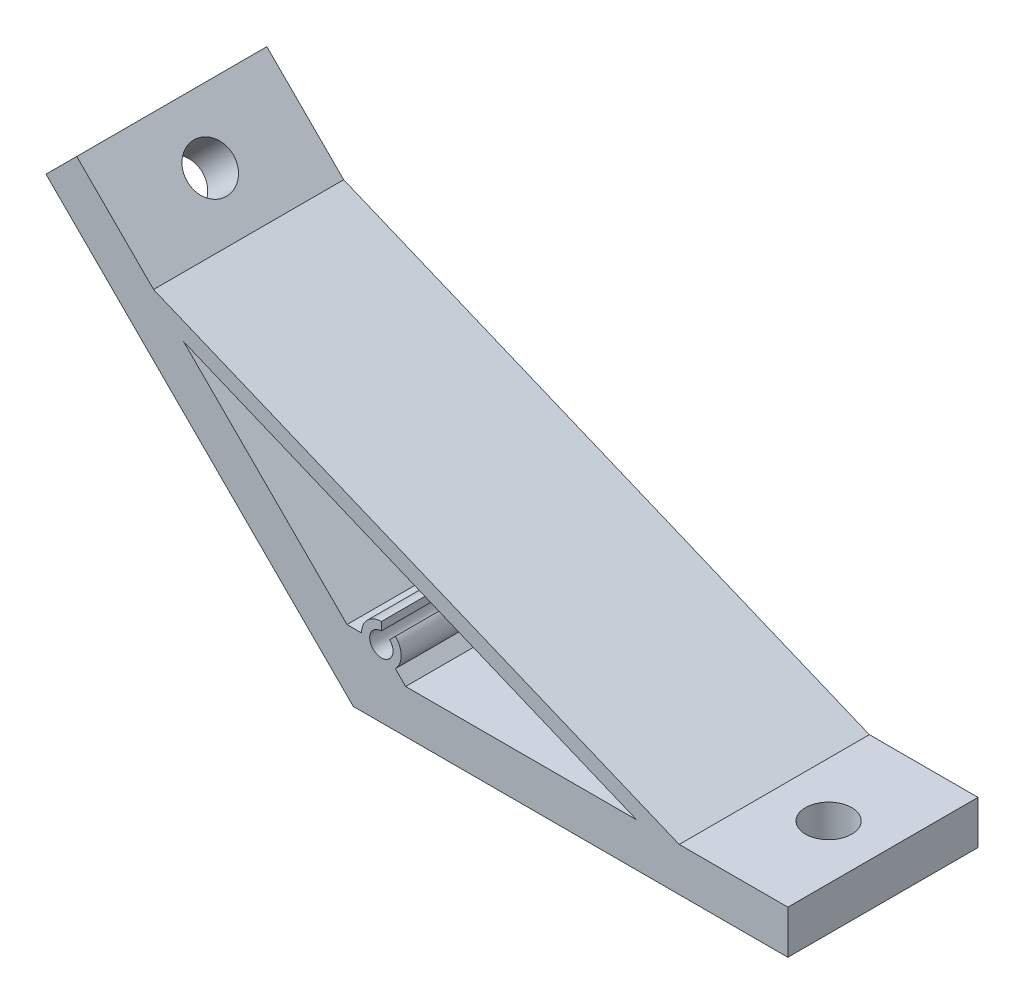
SolidWorks part; units mm, degrees
ref_plane "前视基准面" through (0, 0, 0) normal (0, 0, 1) x (1, 0, 0)
ref_plane "上视基准面" through (0, 0, 0) normal (0, 1, 0) x (1, 0, 0)
ref_plane "右视基准面" through (0, 0, 0) normal (1, 0, 0) x (0, 0, -1)
sketch "草图1" plane through (0, 0, 0) normal (0, 0, 1) x (1, 0, 0)
  line B0 (80, 0) -> (0, 0)
  line B1 (80, 8) -> (60, 8)
  line B2 (52.1606, 8) -> (9.6386, 8)
  line B3 (0, 0) -> (-56.5685, 56.5685)
  line B4 (-1.1587, 12.4724) -> (-31.2263, 42.54)
  line B5 (-36.7696, 48.0833) -> (-50.9117, 62.2254)
  line B6 (-50.9117, 62.2254) -> (-56.5685, 56.5685)
  line B7 (80, 8) -> (80, 0)
  line B8 (-1.1587, 12.4724) -> (1.5162, 12.4724)
  line B9 (9.6386, 8) -> (7.7472, 9.8914)
  line B10 (6.6865, 13.9927) -> (7.7472, 15.0533)
  line B11 (5.1662, 14.6224) -> (5.1662, 16.1224)
  line B12 (-36.7696, 48.0833) -> (60, 8)
  line B13 (-31.2263, 42.54) -> (52.1606, 8)
  arc B14 (5.1662, 14.6224) -> (6.6865, 13.9927) centre (5.1662, 12.4724) ccw
  arc B15 (7.7472, 9.8914) -> (7.7472, 15.0533) centre (5.1662, 12.4724) ccw
  arc B16 (5.1662, 16.1224) -> (1.5162, 12.4724) centre (5.1662, 12.4724) ccw
sketch_block_instance "A$C053212F5-1"
sketch_block "A$C053212F5"
extrude "凸台-拉伸1" add sketch "草图1" along normal mid plane 35
sketch "草图3" plane through (0, 8, 0) normal (0, 1, 0) x (1, 0, 0)
  line L0 (80, -17.5) -> (80, 17.5) construction
  circle A0 centre (70, 0) radius 4.25
  dimension "D1" = 10
extrude "切除-拉伸1" cut sketch "草图3" against normal through all
sketch "草图4" plane through (11.6152, 28.0416, 0) normal (0.3827, 0.9239, 0) x (0.9239, -0.3827, 0)
  line L0 (0, -17.5) -> (0, 17.5) construction
  line L1 (52.3713, -17.5) -> (-52.3713, -17.5) construction
  line L2 (52.3713, 17.5) -> (-52.3713, 17.5) construction
ref_plane "基准面2" through (0, 0, 0) normal (-0.9239, 0.3827, 0) x (0, 0, 1)
mirror "镜向1" about plane through (0, 0, 0) normal (-0.9239, 0.3827, 0) of "切除-拉伸1"
